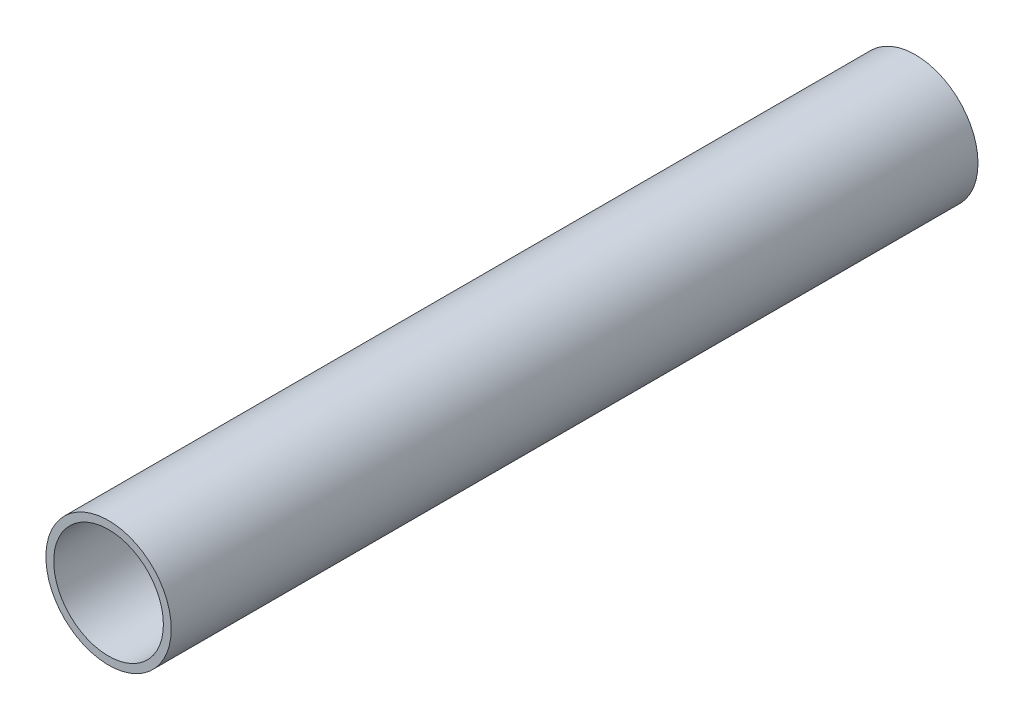
SolidWorks part; units mm, degrees
material "Thornel Mat VMA"
ref_plane "Front Plane" through (0, 0, 0) normal (0, 0, 1) x (1, 0, 0)
ref_plane "Top Plane" through (0, 0, 0) normal (0, 1, 0) x (1, 0, 0)
ref_plane "Right Plane" through (0, 0, 0) normal (1, 0, 0) x (0, 0, -1)
sketch "Sketch1" plane through (0, 0, 0) normal (0, 0, 1) x (1, 0, 0)
  circle A0 centre (0, 0) radius 7
  circle A1 centre (0, 0) radius 8
  dimension "D1" = 16
  dimension "D2" = 14
extrude "Boss-Extrude1" add sketch "Sketch1" along normal blind 103
